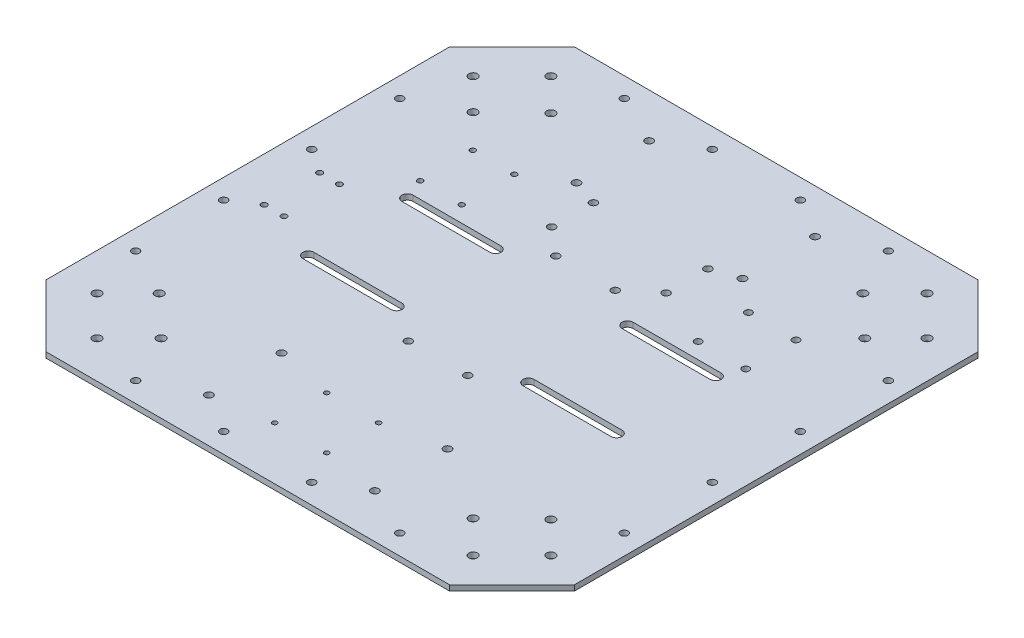
SolidWorks part; units mm, degrees
ref_plane "Front Plane" through (0, 0, 0) normal (0, 0, 1) x (1, 0, 0)
ref_plane "Top Plane" through (0, 0, 0) normal (0, 1, 0) x (1, 0, 0)
ref_plane "Right Plane" through (0, 0, 0) normal (1, 0, 0) x (0, 0, -1)
sketch "Sketch1" plane through (0, 0, 0) normal (0, 1, 0) x (1, 0, 0)
  line L0 (-61.766, 15.7353) -> (-25.845, 51.6564)
  line L1 (-61.766, 51.6564) -> (243.034, 51.6564)
  line L2 (-61.766, 51.6564) -> (-61.766, -253.1436)
  line L3 (-61.766, -253.1436) -> (243.034, -253.1436)
  line L4 (243.034, 51.6564) -> (243.034, -253.1436)
  line L5 (90.634, 95.069) -> (90.634, -294.9418) construction
  line L6 (-86.5248, -100.7436) -> (277.558, -100.7436) construction
  line L7 (243.034, 15.7353) -> (207.1129, 51.6564)
  line L8 (243.034, -217.2226) -> (207.1129, -253.1436)
  line L9 (-61.766, -217.2226) -> (-25.845, -253.1436)
  line L10 (128.734, -72.1686) -> (179.534, -72.1686) construction
  line L11 (128.734, -68.9936) -> (179.534, -68.9936)
  line L12 (128.734, -75.3436) -> (179.534, -75.3436)
  line L13 (128.734, -129.3186) -> (179.534, -129.3186) construction
  line L14 (128.734, -132.4936) -> (179.534, -132.4936)
  line L15 (128.734, -126.1436) -> (179.534, -126.1436)
  line L16 (52.534, -129.3186) -> (1.734, -129.3186) construction
  line L17 (52.534, -132.4936) -> (1.734, -132.4936)
  line L18 (52.534, -126.1436) -> (1.734, -126.1436)
  line L19 (52.534, -72.1686) -> (1.734, -72.1686) construction
  line L20 (52.534, -68.9936) -> (1.734, -68.9936)
  line L21 (52.534, -75.3436) -> (1.734, -75.3436)
  arc A0 (128.734, -68.9936) -> (128.734, -75.3436) centre (128.734, -72.1686) ccw
  arc A1 (179.534, -75.3436) -> (179.534, -68.9936) centre (179.534, -72.1686) ccw
  arc A2 (128.734, -132.4936) -> (128.734, -126.1436) centre (128.734, -129.3186) cw
  arc A3 (179.534, -126.1436) -> (179.534, -132.4936) centre (179.534, -129.3186) cw
  arc A4 (52.534, -132.4936) -> (52.534, -126.1436) centre (52.534, -129.3186) ccw
  arc A5 (1.734, -126.1436) -> (1.734, -132.4936) centre (1.734, -129.3186) ccw
  arc A6 (52.534, -68.9936) -> (52.534, -75.3436) centre (52.534, -72.1686) cw
  arc A7 (1.734, -75.3436) -> (1.734, -68.9936) centre (1.734, -72.1686) cw
  point P8 (90.634, 51.6564)
  point P11 (-61.766, -100.7436)
  point P18 (154.134, -72.1686)
  point P27 (154.134, -129.3186)
  point P34 (27.134, -129.3186)
  point P41 (27.134, -72.1686)
  dimension "D6" = 6.35
  dimension "D1" = 304.8
  dimension "D2" = 304.8
  dimension "D3" = 45
  dimension "D4" = 50.8
  dimension "D5" = 50.8
  dimension "D7" = 38.1
  dimension "D8" = 50.8
extrude "Boss-Extrude1" add sketch "Sketch1" along normal blind 3.175 contours L2 L9 L3 L8 L4 L7 L1 L0 A5 L18 A4 L17 A1 L12 A0 L11 L15 A3 L14 A2 L21 A7 L20 A6
sketch "Sketch2" plane through (0, 3.175, 0) normal (0, 1, 0) x (1, 0, 0)
  line L0 (-40.323, 7.7627) -> (-22.3625, -10.1978) construction
  line L1 (-17.8724, 30.2133) -> (0.6409, 11.7001) construction
  line L2 (-43.8055, 33.6958) -> (20.8232, -30.9329) construction
  line L3 (-61.766, 15.7353) -> (-25.845, 51.6564) construction
  line L7 (90.634, 51.6564) -> (90.634, -253.1436) construction
  line L8 (-25.845, 51.6564) -> (207.1129, 51.6564) construction
  line L9 (-25.845, -253.1436) -> (207.1129, -253.1436) construction
  line L10 (-61.766, -100.7436) -> (243.034, -100.7436) construction
  line L11 (-61.766, 15.7353) -> (-61.766, -217.2226) construction
  line L12 (243.034, 15.7353) -> (243.034, -217.2226) construction
  circle A0 centre (-17.8724, 30.2133) radius 2.4638
  circle A1 centre (0.6409, 11.7001) radius 2.4638
  circle A2 centre (-22.3625, -10.1978) radius 2.4638
  circle A3 centre (-40.323, 7.7627) radius 2.4638
  circle A4 centre (203.6304, -10.1978) radius 2.4638
  circle A5 centre (221.5909, 7.7627) radius 2.4638
  circle A6 centre (180.627, 11.7001) radius 2.4638
  circle A7 centre (199.1403, 30.2133) radius 2.4638
  circle A8 centre (-22.3625, -191.2895) radius 2.4638
  circle A9 centre (-40.323, -209.25) radius 2.4638
  circle A10 centre (-17.8724, -231.7006) radius 2.4638
  circle A11 centre (0.6409, -213.1873) radius 2.4638
  circle A12 centre (221.5909, -209.25) radius 2.4638
  circle A13 centre (199.1403, -231.7006) radius 2.4638
  circle A14 centre (180.627, -213.1873) radius 2.4638
  circle A15 centre (203.6304, -191.2895) radius 2.4638
  dimension "D3" = 4.9276
  dimension "D4" = 4.9276
  dimension "D5" = 4.9276
  dimension "D6" = 4.9276
  dimension "D1" = 25.4
  dimension "D2" = 31.75
  dimension "D7" = 15.875
extrude "Cut-Extrude1" cut sketch "Sketch2" against normal blind 6.35
sketch "Sketch3" plane through (0, 3.175, 0) normal (0, 1, 0) x (1, 0, 0)
  line L0 (-61.766, -100.7436) -> (278.5513, -100.7436) construction
  line L2 (-61.766, 15.7353) -> (-61.766, -217.2226) construction
  line L3 (90.634, 51.6564) -> (90.634, -273.1997) construction
  line L4 (-25.845, 51.6564) -> (207.1129, 51.6564) construction
  circle A0 centre (73.362, -58.1986) radius 2.159
  circle A1 centre (107.652, -58.1986) radius 2.159
  circle A2 centre (73.362, -143.2886) radius 2.159
  circle A3 centre (107.652, -143.2886) radius 2.159
  point P10 (-61.766, -100.7436)
  dimension "D3" = 4.318
  dimension "D4" = 4.318
  dimension "D5" = 4.318
  dimension "D6" = 4.318
  dimension "D1" = 34.29
  dimension "D2" = 85.09
  dimension "D7" = 42.545
  dimension "D8" = 17.272
extrude "Cut-Extrude2" cut sketch "Sketch3" against normal blind 6.35
sketch "Sketch4" plane through (0, 3.175, 0) normal (0, 1, 0) x (1, 0, 0)
  line L0 (90.634, 51.6564) -> (90.634, -36.4614) construction
  line L1 (-25.845, 51.6564) -> (207.1129, 51.6564) construction
  line L2 (-61.766, -100.7436) -> (257.447, -100.7436) construction
  line L3 (-61.766, 15.7353) -> (-61.766, -217.2226) construction
  circle A0 centre (42.755, 26.2564) radius 2.2225
  circle A1 centre (138.513, 26.2564) radius 2.2225
  circle A2 centre (42.755, -15.6536) radius 2.2225
  circle A3 centre (138.513, -15.6536) radius 2.2225
  circle A4 centre (138.513, -185.8336) radius 2.2225
  circle A5 centre (42.755, -185.8336) radius 2.2225
  circle A6 centre (138.513, -227.7436) radius 2.2225
  circle A7 centre (42.755, -227.7436) radius 2.2225
  dimension "D1" = 4.445
  dimension "D2" = 4.445
  dimension "D3" = 4.445
  dimension "D4" = 4.445
  dimension "D5" = 95.758
  dimension "D6" = 41.91
  dimension "D7" = 47.879
  dimension "D8" = 25.4
extrude "Cut-Extrude3" cut sketch "Sketch4" against normal through all
sketch "Sketch5" plane through (0, 3.175, 0) normal (0, 1, 0) x (1, 0, 0)
  line L0 (-61.766, -100.7436) -> (105.2484, -100.7436) construction
  line L1 (-61.766, 15.7353) -> (-61.766, -217.2226) construction
  circle A0 centre (-36.366, -84.7416) radius 1.651
  circle A1 centre (-24.936, -84.7416) radius 1.651
  circle A2 centre (-24.936, -116.7456) radius 1.651
  circle A3 centre (-36.366, -116.7456) radius 1.651
  dimension "D1" = 3.302
  dimension "D2" = 3.302
  dimension "D3" = 11.43
  dimension "D4" = 16.002
  dimension "D5" = 25.4
extrude "Cut-Extrude4" cut sketch "Sketch5" against normal through all
sketch "Sketch6" plane through (0, 3.175, 0) normal (0, 1, 0) x (1, 0, 0)
  line L0 (243.034, 15.7353) -> (243.034, -217.2226) construction
  line L1 (-25.845, 51.6564) -> (207.1129, 51.6564) construction
  line L2 (90.634, 51.6564) -> (90.634, -253.1436) construction
  line L3 (-25.845, -253.1436) -> (207.1129, -253.1436) construction
  line L4 (-61.766, 15.7353) -> (-61.766, -217.2226) construction
  circle A0 centre (157.182, -30.8936) radius 2.032
  circle A1 centre (157.182, -59.8496) radius 2.032
  circle A2 centre (184.614, -59.8496) radius 2.032
  circle A3 centre (184.614, -30.8936) radius 2.032
  circle A4 centre (57.614, -20.7336) radius 2.159
  circle A5 centre (57.614, -44.8636) radius 2.159
  circle A6 centre (123.654, -44.8636) radius 2.159
  circle A7 centre (123.654, -20.7336) radius 2.159
  circle A8 centre (75.648, -192.6916) radius 1.397
  circle A9 centre (75.648, -222.6636) radius 1.397
  circle A10 centre (105.62, -222.6636) radius 1.397
  circle A11 centre (105.62, -192.6916) radius 1.397
  circle A12 centre (-3.389, -29.3696) radius 1.55
  circle A13 centre (-3.346, -59.7696) radius 1.55
  circle A14 centre (20.6111, -29.3696) radius 1.55
  circle A15 centre (20.6111, -59.7696) radius 1.55
  dimension "D1" = 4.064
  dimension "D6" = 4.318
  dimension "D7" = 4.318
  dimension "D10" = 2.794
  dimension "D11" = 2.794
  dimension "D15" = 3.1
  dimension "D16" = 3.1
  dimension "D18" = 3.1
  dimension "D19" = 3.1
  dimension "D2" = 27.432
  dimension "D3" = 28.956
  dimension "D4" = 58.42
  dimension "D5" = 82.55
  dimension "D8" = 33.02
  dimension "D9" = 24.13
  dimension "D12" = 14.986
  dimension "D13" = 29.972
  dimension "D14" = 30.48
  dimension "D17" = 30.4
  dimension "D20" = 24
  dimension "D21" = 72.39
  dimension "D22" = 58.42
  dimension "D23" = 81.026
extrude "Cut-Extrude5" cut sketch "Sketch6" against normal through all
sketch "Sketch7" plane through (0, 3.175, 0) normal (0, 1, 0) x (1, 0, 0)
  line L0 (90.634, 51.6564) -> (90.634, -272.7763) construction
  line L1 (-25.845, 51.6564) -> (207.1129, 51.6564) construction
  line L2 (-61.766, -100.7436) -> (338.9555, -100.7436) construction
  line L3 (-61.766, 15.7353) -> (-61.766, -217.2226) construction
  circle A0 centre (65.234, 40.2264) radius 2.159
  circle A1 centre (14.434, 40.2264) radius 2.159
  circle A2 centre (-50.336, -75.3436) radius 2.159
  circle A3 centre (-50.336, -24.5436) radius 2.159
  circle A4 centre (231.604, -24.5436) radius 2.159
  circle A5 centre (231.604, -75.3436) radius 2.159
  circle A6 centre (166.834, 40.2264) radius 2.159
  circle A7 centre (116.034, 40.2264) radius 2.159
  circle A8 centre (116.034, -241.7136) radius 2.159
  circle A9 centre (166.834, -241.7136) radius 2.159
  circle A10 centre (231.604, -126.1436) radius 2.159
  circle A11 centre (231.604, -176.9436) radius 2.159
  circle A12 centre (-50.336, -176.9436) radius 2.159
  circle A13 centre (-50.336, -126.1436) radius 2.159
  circle A14 centre (14.434, -241.7136) radius 2.159
  circle A15 centre (65.234, -241.7136) radius 2.159
  dimension "D1" = 4.318
  dimension "D2" = 4.318
  dimension "D6" = 4.318
  dimension "D7" = 4.318
  dimension "D3" = 25.4
  dimension "D4" = 50.8
  dimension "D5" = 11.43
  dimension "D8" = 25.4
  dimension "D9" = 50.8
  dimension "D10" = 11.43
extrude "Cut-Extrude6" cut sketch "Sketch7" against normal through all
